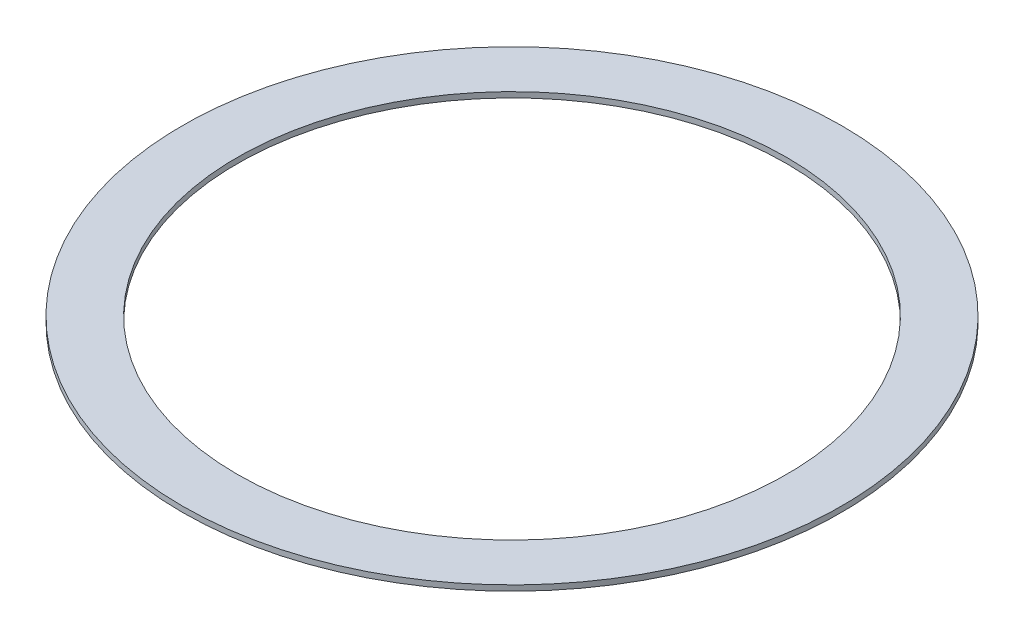
SolidWorks part; units mm, degrees
material "Plain Carbon Steel"
ref_plane "Front Plane" through (0, 0, 0) normal (0, 0, 1) x (1, 0, 0)
ref_plane "Top Plane" through (0, 0, 0) normal (0, 1, 0) x (1, 0, 0)
ref_plane "Right Plane" through (0, 0, 0) normal (1, 0, 0) x (0, 0, -1)
sketch "Sketch1" plane through (0, 0, 0) normal (0, 0, 1) x (1, 0, 0)
  line L0 (0, 0) -> (0, 26.4445) construction
  line L2 (2.5, 4.1692) -> (3, 4.1692)
  line L3 (2.5, 4.1692) -> (2.5, 4.2192)
  line L4 (2.5, 4.2192) -> (3, 4.2192)
  line L5 (3, 4.1692) -> (3, 4.2192)
  dimension "D1" = 0.5
  dimension "D2" = 0.05
  dimension "D3" = 2.5
revolve "Revolve1" add sketch "Sketch1" angle 360 about L0
